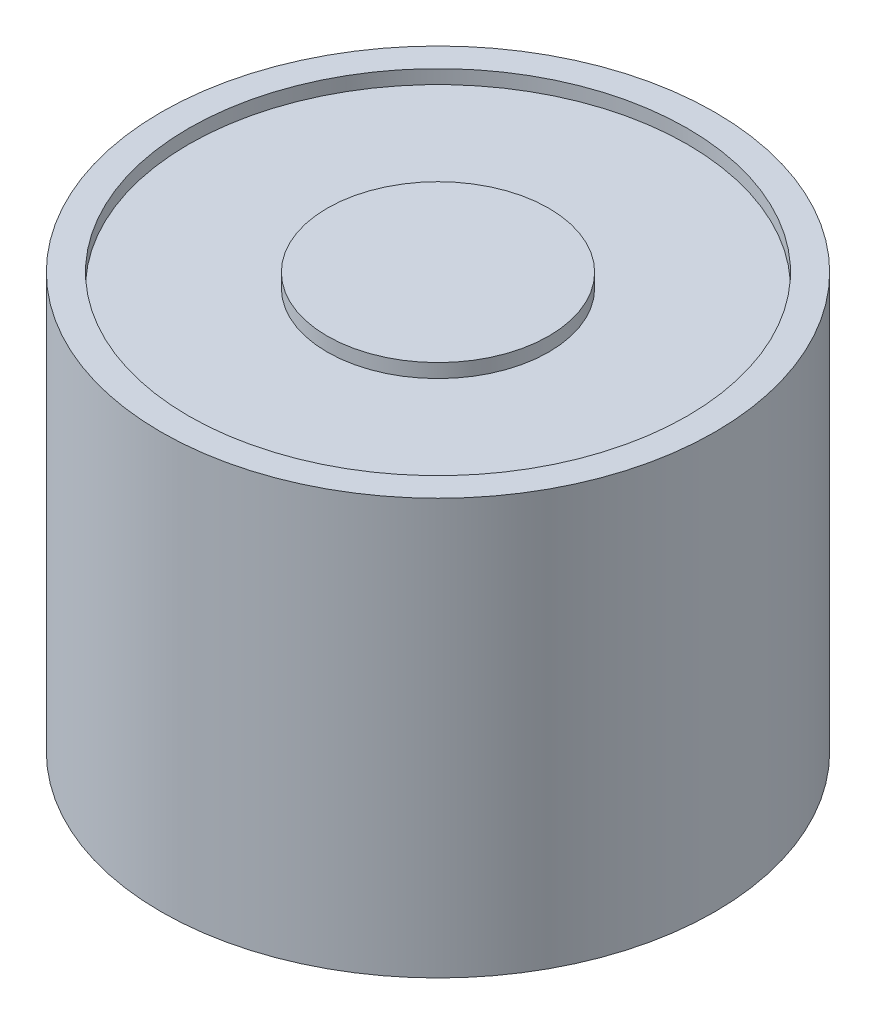
SolidWorks part; units mm, degrees
ref_plane "Front Plane" through (0, 0, 0) normal (0, 0, 1) x (1, 0, 0)
ref_plane "Top Plane" through (0, 0, 0) normal (0, 1, 0) x (1, 0, 0)
ref_plane "Right Plane" through (0, 0, 0) normal (1, 0, 0) x (0, 0, -1)
sketch "Sketch1" plane through (0, 0, 0) normal (0, 1, 0) x (1, 0, 0)
  circle A0 centre (0, 0) radius 10
  dimension "D1" = 20
extrude "Boss-Extrude1" add sketch "Sketch1" along normal blind 15
sketch "Sketch2" plane through (0, 15, 0) normal (0, 1, 0) x (1, 0, 0)
  circle A0 centre (0, 0) radius 9
  circle A1 centre (0, 0) radius 4
  circle A2 centre (0, 0) radius 10 construction
  dimension "D1" = 1
  dimension "D2" = 8
extrude "Cut-Extrude1" cut sketch "Sketch2" against normal blind 0.5
hole_wizard "M2.5x0.45 Tapped Hole1" positions "Sketch4" profile "Sketch3" tap size "M2.5x0.45" standard "ANSI Metric"
sketch "Sketch4" plane through (0, 0, 0) normal (0, -1, 0) x (-1, 0, 0)
  point P1 (0, 0)
  point P6 (0, 0)
  point P7 (0, 0)
sketch "Sketch3" plane through (0, 0, 0) normal (1, 0, 0) x (0, 0, -1)
  line L0 (0, 0) -> (0, 6.9659)
  line L1 (0, 6.9659) -> (1.025, 6.35)
  line L2 (1.025, 6.35) -> (1.025, 0)
  line L5 (1.025, 0) -> (0, 0)
  line L10 (0, 6.9659) -> (-1.025, 6.35) construction
  line L11 (0, -6.35) -> (0, 107.95) construction
  dimension "Tap Drill Dia." = 2.05
  dimension "Tap Drill Depth" = 6.35
  dimension "Drill Angle" = 118
cosmetic thread "Hole Thread2" parameters "D1"=5, "D2"=2.5
